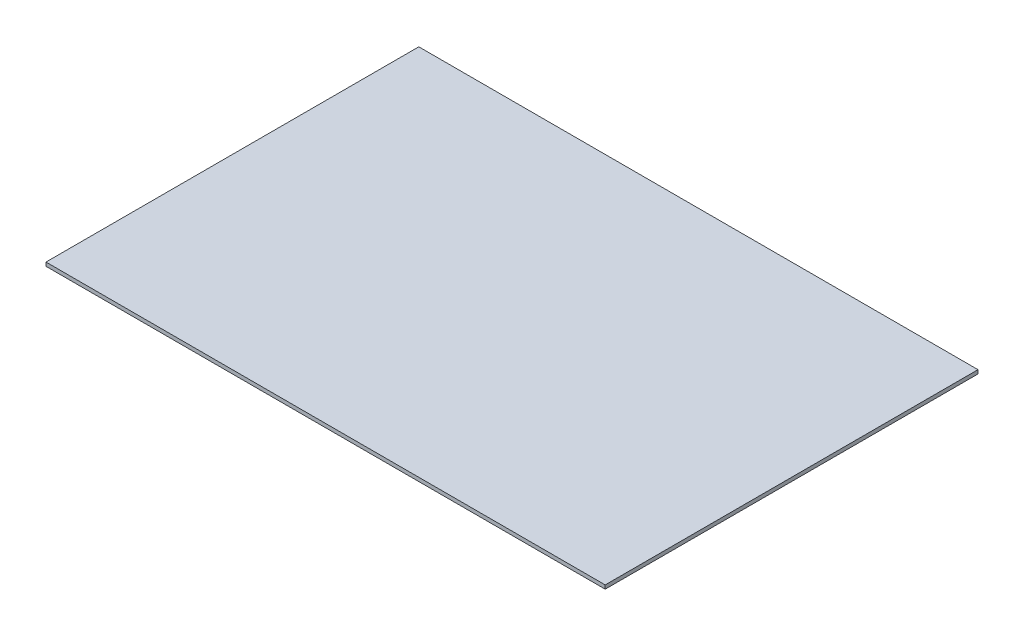
SolidWorks part; units mm, degrees
material "Polyurethane Foam Rigid"
ref_plane "Front Plane" through (0, 0, 0) normal (0, 0, 1) x (1, 0, 0)
ref_plane "Top Plane" through (0, 0, 0) normal (0, 1, 0) x (1, 0, 0)
ref_plane "Right Plane" through (0, 0, 0) normal (1, 0, 0) x (0, 0, -1)
sketch "Sketch1" plane through (0, 0, 0) normal (0, 1, 0) x (1, 0, 0)
  line L1 (-750, 500) -> (750, 500)
  line L2 (-750, 500) -> (-750, -500)
  line L3 (-750, -500) -> (750, -500)
  line L4 (750, 500) -> (750, -500)
  line L5 (-750, 500) -> (750, -500) construction
  line L6 (-750, -500) -> (750, 500) construction
  point P0 (0, 0)
  dimension "D1" = 1500
  dimension "D2" = 1000
extrude "Boss-Extrude1" add sketch "Sketch1" along normal mid plane 10
